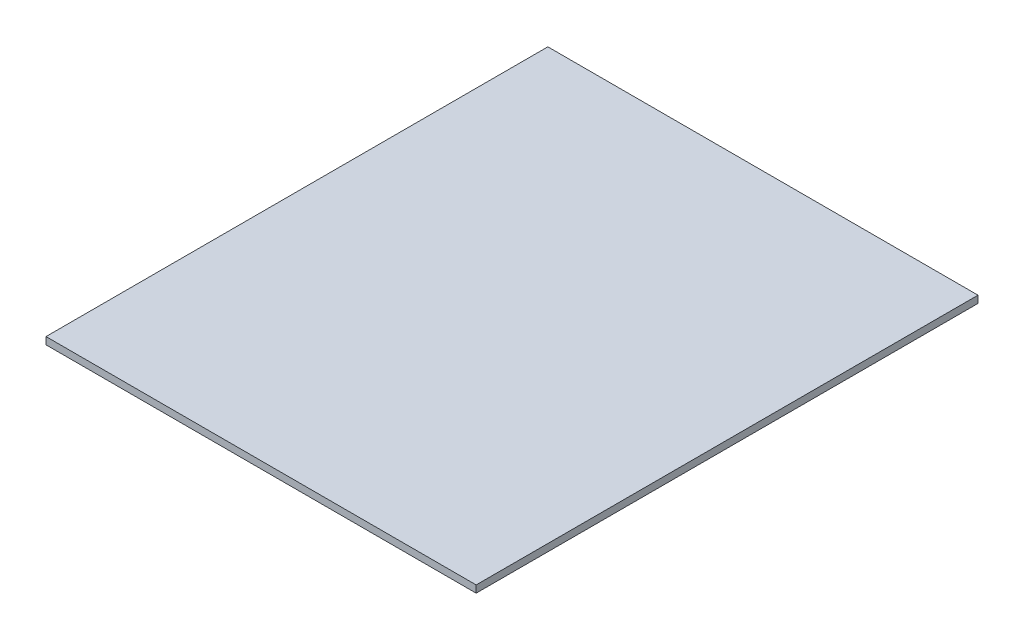
SolidWorks part; units mm, degrees
material "Concreto"
ref_plane "Plano frontal" through (0, 0, 0) normal (0, 0, 1) x (1, 0, 0)
ref_plane "Plano superior" through (0, 0, 0) normal (0, 1, 0) x (1, 0, 0)
ref_plane "Plano direito" through (0, 0, 0) normal (1, 0, 0) x (0, 0, -1)
sketch "Esboço1" plane through (0, 0, 0) normal (0, 1, 0) x (1, 0, 0)
  line L1 (-1500, 1750) -> (1500, 1750)
  line L2 (-1500, 1750) -> (-1500, -1750)
  line L3 (-1500, -1750) -> (1500, -1750)
  line L4 (1500, 1750) -> (1500, -1750)
  line L5 (-1500, 1750) -> (1500, -1750) construction
  line L6 (-1500, -1750) -> (1500, 1750) construction
  point P0 (0, 0)
  dimension "D1" = 3500
  dimension "D2" = 3000
extrude "Ressalto-extrusão1" add sketch "Esboço1" along normal blind 50
